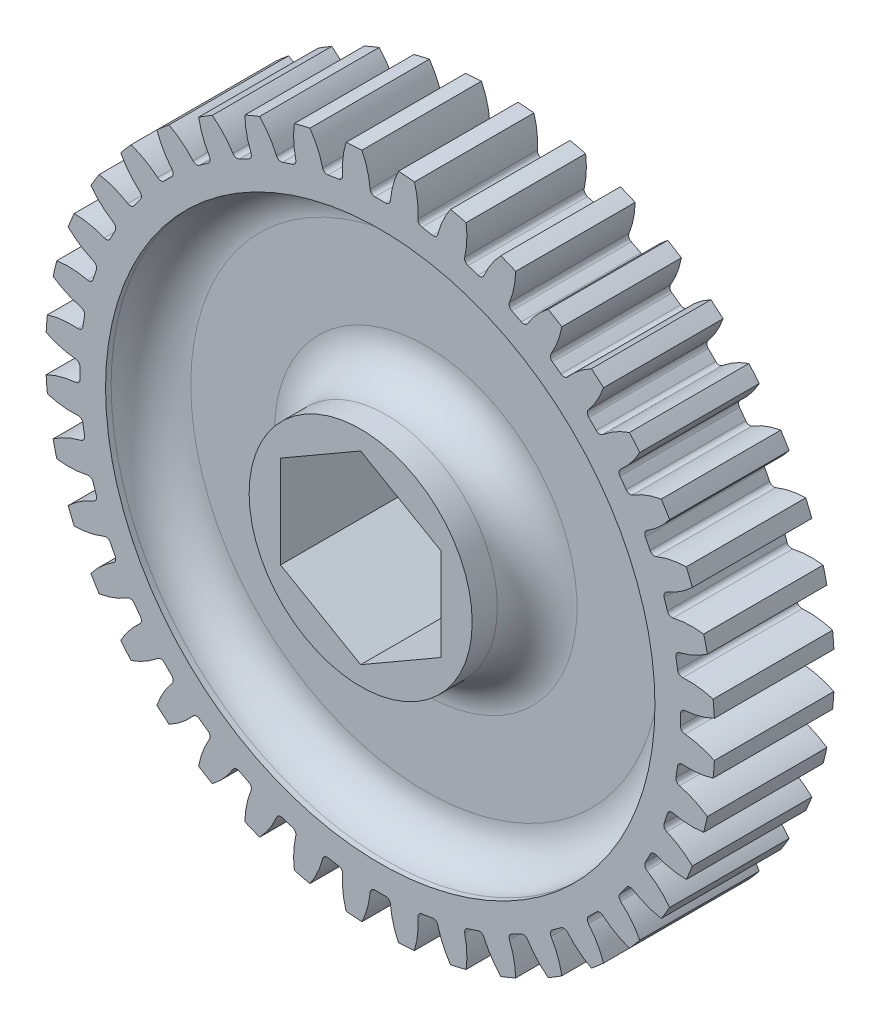
SolidWorks part; units mm, degrees
material "AISI 4130 Acero normalizado a 870C"
ref_plane "Alzado" through (0, 0, 0) normal (0, 0, 1) x (1, 0, 0)
ref_plane "Planta" through (0, 0, 0) normal (0, 1, 0) x (1, 0, 0)
ref_plane "Vista lateral" through (0, 0, 0) normal (1, 0, 0) x (0, 0, -1)
sketch "Croquis1" plane through (0, 0, 0) normal (0, 0, 1) x (1, 0, 0)
  circle A0 centre (0, 0) radius 25.4 construction
  circle A1 centre (0, 0) radius 26.67
  dimension "D" = 50.8
  dimension "OD" = 53.34
extrude "Saliente-Extruir1" add sketch "Croquis1" along normal mid plane 9.525
sketch "Croquis2" plane through (0, 0, 0) normal (0, 0, 1) x (1, 0, 0)
  line L0 (0, 0) -> (0, 26.67) construction
  line L1 (0, 0) -> (4.1721, 26.3416) construction
  line L2 (0, 0) -> (2.0925, 26.5878) construction
  line L3 (-0.7866, 23.9177) -> (0, 0) construction
  line L4 (-0.9972, 25.3804) -> (0.9972, 25.3804) construction
  line L5 (0.9972, 25.3804) -> (2.9854, 25.2239) construction
  line L6 (-1.3222, 26.6372) -> (0, 21.5245) construction
  circle A0 centre (0, 0) radius 26.67 construction
  arc A2 (0.7866, 23.9177) -> (-0.7866, 23.9177) centre (0, 0) ccw
  circle A5 centre (0, 0) radius 25.4 construction
  arc A6 (-1.4566, 26.6302) -> (-0.7866, 23.9177) centre (-7.508, 23.6966) cw
  arc A7 (1.4566, 26.6302) -> (0.7866, 23.9177) centre (7.508, 23.6966) ccw
  arc A8 (1.4566, 26.6302) -> (-1.4566, 26.6302) centre (0, 0) ccw
  dimension "D1" = 9
  dimension "D2" = 4.5
  dimension "B" = 1.4694
  dimension "Pressure Angle" = 14.5
extrude "Cortar-Extruir1" cut sketch "Croquis2" against normal through all both and the other way through all
fillet "Redondeo1" radius 0.381 2 edges at (0.7866, 23.9177, 0) (-0.7866, 23.9177, 0)
pattern_circular "MatrizC1" count 40 over 360 about axis through (0, 0, 0) along (0, 0, 1) of "Cortar-Extruir1", "Redondeo1"
sketch "Croquis3" plane through (0, 0, 0) normal (0, 0, 1) x (1, 0, 0)
  circle A0 centre (0, 0) radius 8.89
  dimension "sp" = 17.78
extrude "Saliente-Extruir2" add sketch "Croquis3" along normal mid plane 12.6492
sketch "Croquis4" plane through (0, 0, 0) normal (0, 0, 1) x (1, 0, 0)
  line L1 (0, 7.3763) -> (-6.3881, 3.6882)
  line L2 (-6.3881, 3.6882) -> (-6.3881, -3.6882)
  line L3 (-6.3881, -3.6882) -> (0, -7.3763)
  line L4 (0, -7.3763) -> (6.3881, -3.6882)
  line L5 (6.3881, -3.6882) -> (6.3881, 3.6882)
  line L6 (6.3881, 3.6882) -> (0, 7.3763)
  circle A0 centre (0, 0) radius 6.3881 construction
  dimension "D1" = 12.7762
extrude "Cortar-Extruir2" cut sketch "Croquis4" against normal through all both and the other way through all
sketch "Croquis7" plane through (0, 0, 0) normal (0, 0, 1) x (1, 0, 0)
  circle A0 centre (0, 0) radius 21.8948
  circle A1 centre (0, 0) radius 8.89
  circle A5 centre (0, 0) radius 26.67 construction
  circle A6 centre (0, 0) radius 8.89 construction
  dimension "D1" = 4.7752
extrude "Cortar-Extruir5" cut sketch "Croquis7" against normal through all from offset 1.143 offset against normal yes
fillet "Redondeo2" radius 3.175 2 edges at (8.89, 0, -1.143) (21.8948, 0, -1.143)
mirror "Simetría1" about plane through (0, 0, 0) normal (0, 0, 1) of "Redondeo2", "Cortar-Extruir5"
equation "\"Number of teeth\"=40"
equation "\"Diametral Pitch\"= 20"
equation "\"Pressure Angle\"= 14.5"
equation "\"D@Croquis1\"=\"Number of teeth\"/\"Diametral Pitch\""
equation "\"OD@Croquis1\"=(\"Number of teeth\"+2) /\"Diametral Pitch\""
equation "\"D2@Croquis2\"=(360 / \"Number of teeth\")/ 2."
equation "\"D1@Croquis2\"=360 / \"Number of teeth\""
equation "\"B@Croquis2\"=1.157 / \"Diametral Pitch\""
equation "\"Pressure Angle@Croquis2\" = \"Pressure Angle\""
equation "\"D1@Redondeo1\"=(pi / \"Diametral Pitch\") * .0955"
equation "\"D1@MatrizC1\"=\"Number of teeth\""
equation "\"Tt@Saliente-Extruir1\"=if( \"Number of teeth\"=>30,0.375,0.475)"
equation "\"sp@Croquis3\"=if( \"Number of teeth\"=16,0.65,0.7)"
